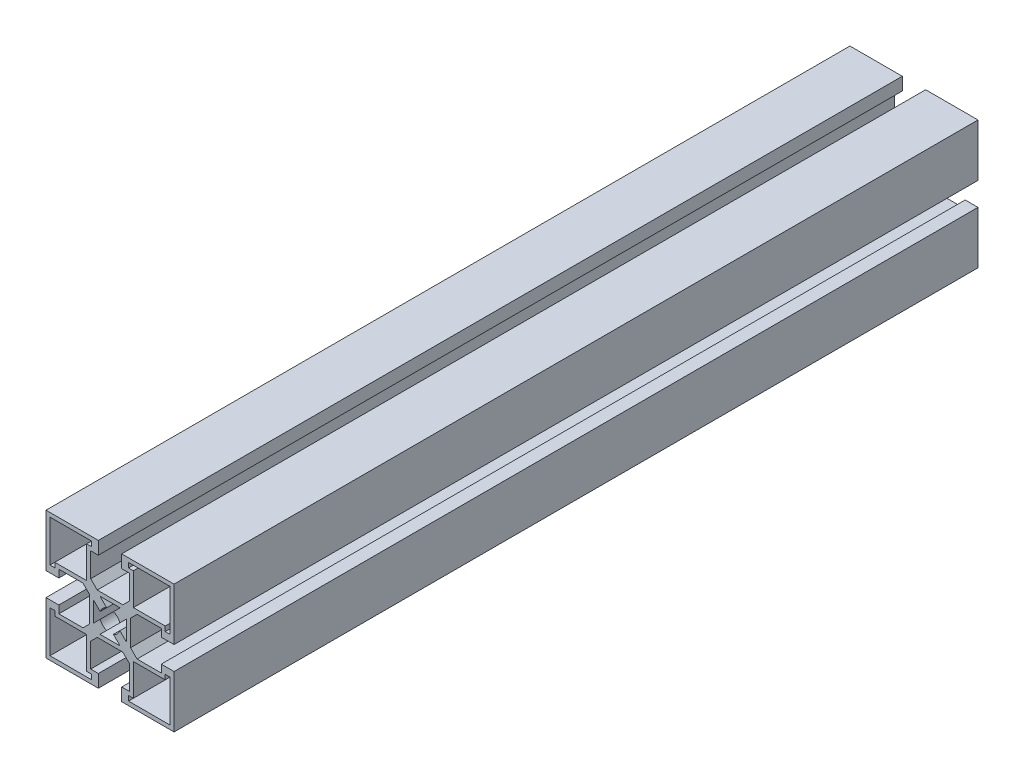
SolidWorks part; units mm, degrees
material "6061 Alloy"
ref_plane "Front Plane" through (0, 0, 0) normal (0, 0, 1) x (1, 0, 0)
ref_plane "Top Plane" through (0, 0, 0) normal (0, 1, 0) x (1, 0, 0)
ref_plane "Right Plane" through (0, 0, 0) normal (1, 0, 0) x (0, 0, -1)
sketch "Sketch1" plane through (0, 0, 0) normal (0, 0, 1) x (1, 0, 0)
  line L18 (8.2, 8.2) -> (8.2, 19.4)
  line L20 (19.4, 8.2) -> (8.2, 8.2)
  line L21 (19.4, 6.5) -> (19.4, 8.2)
  line L22 (21.1, 6.5) -> (19.4, 6.5)
  line L23 (21.1, 21.1) -> (21.1, 6.5)
  line L24 (6.5, 21.1) -> (21.1, 21.1)
  line L25 (6.5, 19.4) -> (6.5, 21.1)
  line L26 (8.2, 19.4) -> (6.5, 19.4)
  line L27 (-19.4, 6.5) -> (-21.1, 6.5)
  line L28 (-19.4, 8.2) -> (-19.4, 6.5)
  line L29 (-8.2, 8.2) -> (-19.4, 8.2)
  line L31 (-8.2, 19.4) -> (-8.2, 8.2)
  line L32 (-6.5, 19.4) -> (-8.2, 19.4)
  line L33 (-6.5, 21.1) -> (-6.5, 19.4)
  line L34 (-21.1, 21.1) -> (-6.5, 21.1)
  line L35 (-21.1, 6.5) -> (-21.1, 21.1)
  line L88 (-22.5, -22.5) -> (-4.1, -22.5)
  line L89 (-4.1, -22.5) -> (-4.1, -18)
  line L90 (-4.1, -18) -> (-6.8, -18)
  line L91 (-6.8, -18) -> (-6.8, -9.5)
  line L92 (-6.8, -9.5) -> (-4.5, -7.2)
  line L93 (-4.5, -7.2) -> (4.5, -7.2)
  line L94 (4.5, -7.2) -> (6.8, -9.5)
  line L95 (6.8, -9.5) -> (6.8, -18)
  line L96 (6.8, -18) -> (4.1, -18)
  line L97 (4.1, -18) -> (4.1, -22.5)
  line L98 (4.1, -22.5) -> (22.5, -22.5)
  line L99 (22.5, -22.5) -> (22.5, -4.1)
  line L100 (22.5, -4.1) -> (18, -4.1)
  line L101 (18, -4.1) -> (18, -6.8)
  line L102 (18, -6.8) -> (9.5, -6.8)
  line L103 (9.5, -6.8) -> (7.2, -4.5)
  line L104 (7.2, -4.5) -> (7.2, 4.5)
  line L105 (7.2, 4.5) -> (9.5, 6.8)
  line L106 (9.5, 6.8) -> (18, 6.8)
  line L107 (18, 6.8) -> (18, 4.1)
  line L108 (18, 4.1) -> (22.5, 4.1)
  line L109 (22.5, 4.1) -> (22.5, 22.5)
  line L110 (22.5, 22.5) -> (4.1, 22.5)
  line L111 (4.1, 22.5) -> (4.1, 18)
  line L112 (4.1, 18) -> (6.8, 18)
  line L113 (6.8, 18) -> (6.8, 9.5)
  line L114 (6.8, 9.5) -> (4.5, 7.2)
  line L115 (4.5, 7.2) -> (-4.5, 7.2)
  line L116 (-4.5, 7.2) -> (-6.8, 9.5)
  line L117 (-6.8, 9.5) -> (-6.8, 18)
  line L118 (-6.8, 18) -> (-4.1, 18)
  line L119 (-4.1, 18) -> (-4.1, 22.5)
  line L120 (-4.1, 22.5) -> (-22.5, 22.5)
  line L121 (-22.5, 22.5) -> (-22.5, 4.1)
  line L122 (-22.5, 4.1) -> (-18, 4.1)
  line L123 (-18, 4.1) -> (-18, 6.8)
  line L124 (-18, 6.8) -> (-9.5, 6.8)
  line L125 (-9.5, 6.8) -> (-7.2, 4.5)
  line L126 (-7.2, 4.5) -> (-7.2, -4.5)
  line L127 (-7.2, -4.5) -> (-9.5, -6.8)
  line L128 (-9.5, -6.8) -> (-18, -6.8)
  line L129 (-18, -6.8) -> (-18, -4.1)
  line L130 (-18, -4.1) -> (-22.5, -4.1)
  line L131 (-22.5, -4.1) -> (-22.5, -22.5)
  line L133 (-6.5, -21.1) -> (-21.1, -21.1)
  line L134 (-6.5, -19.4) -> (-6.5, -21.1)
  line L135 (-8.2, -19.4) -> (-6.5, -19.4)
  line L136 (-8.2, -8.2) -> (-8.2, -19.4)
  line L138 (-19.4, -8.2) -> (-8.2, -8.2)
  line L139 (-19.4, -6.5) -> (-19.4, -8.2)
  line L140 (-21.1, -6.5) -> (-19.4, -6.5)
  line L141 (-21.1, -21.1) -> (-21.1, -6.5)
  line L151 (6.5, -19.4) -> (8.2, -19.4)
  line L152 (6.5, -21.1) -> (6.5, -19.4)
  line L153 (21.1, -21.1) -> (6.5, -21.1)
  line L154 (21.1, -6.5) -> (21.1, -21.1)
  line L155 (19.4, -6.5) -> (21.1, -6.5)
  line L156 (19.4, -8.2) -> (19.4, -6.5)
  line L157 (8.2, -8.2) -> (19.4, -8.2)
  line L159 (8.2, -19.4) -> (8.2, -8.2)
  line L172 (-5.8, 3.5373) -> (-3.4511, 1.1884)
  line L173 (-5.8, -3.5373) -> (-5.8, 3.5373)
  line L174 (-3.4511, -1.1884) -> (-5.8, -3.5373)
  line L175 (-3.5373, -5.8) -> (-1.1884, -3.4511)
  line L176 (3.5373, -5.8) -> (-3.5373, -5.8)
  line L177 (1.1884, -3.4511) -> (3.5373, -5.8)
  line L178 (5.8, -3.5373) -> (3.4511, -1.1884)
  line L179 (5.8, 3.5373) -> (5.8, -3.5373)
  line L180 (3.4511, 1.1884) -> (5.8, 3.5373)
  line L181 (3.5373, 5.8) -> (1.1884, 3.4511)
  line L182 (-3.5373, 5.8) -> (3.5373, 5.8)
  line L183 (-1.1884, 3.4511) -> (-3.5373, 5.8)
  arc A4 (-1.1884, 3.4511) -> (-3.4511, 1.1884) centre (0, 0) ccw
  arc A5 (-3.4511, -1.1884) -> (-1.1884, -3.4511) centre (0, 0) ccw
  arc A6 (1.1884, -3.4511) -> (3.4511, -1.1884) centre (0, 0) ccw
  arc A7 (3.4511, 1.1884) -> (1.1884, 3.4511) centre (0, 0) ccw
extrude "Boss-Extrude1" add sketch "Sketch1" along normal blind 282.5
